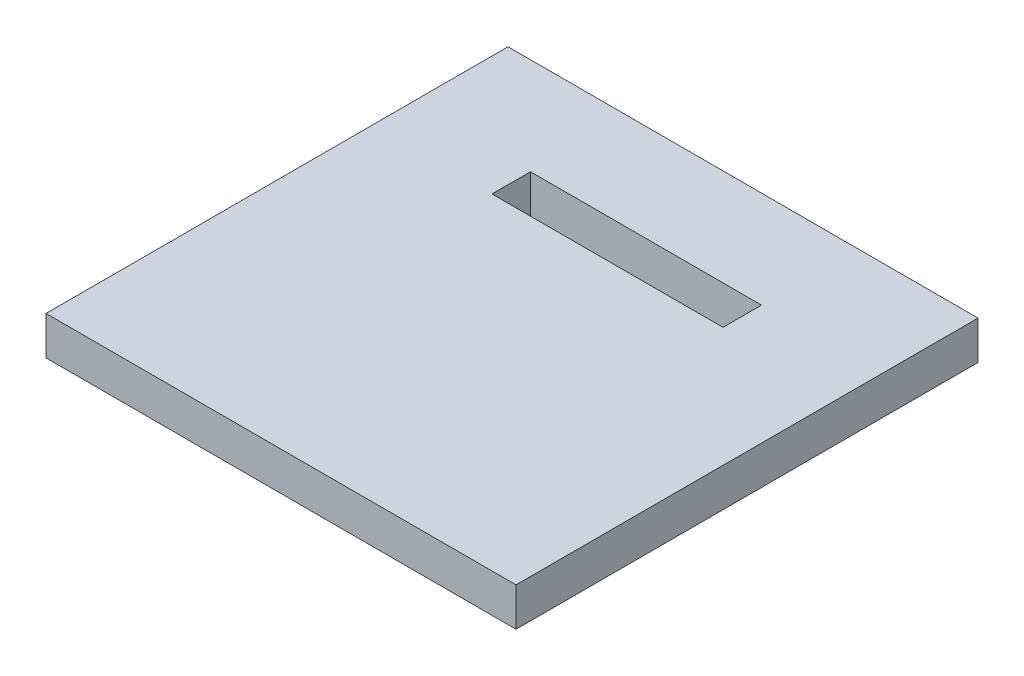
SolidWorks part; units mm, degrees
ref_plane "Front Plane" through (0, 0, 0) normal (0, 0, 1) x (1, 0, 0)
ref_plane "Top Plane" through (0, 0, 0) normal (0, 1, 0) x (1, 0, 0)
ref_plane "Right Plane" through (0, 0, 0) normal (1, 0, 0) x (0, 0, -1)
sketch "Sketch1" plane through (0, 0, 0) normal (0, 1, 0) x (1, 0, 0)
  line L0 (19.3802, 30.099) -> (19.3802, 38.1) construction
  line L1 (0, 0) -> (38.7604, 0)
  line L2 (0, 0) -> (0, 38.1)
  line L3 (0, 38.1) -> (38.7604, 38.1)
  line L4 (38.7604, 0) -> (38.7604, 38.1)
  line L5 (9.8552, 30.099) -> (28.9052, 30.099)
  line L6 (9.8552, 30.099) -> (9.8552, 26.924)
  line L7 (9.8552, 26.924) -> (28.9052, 26.924)
  line L8 (28.9052, 30.099) -> (28.9052, 26.924)
  dimension "D1" = 38.1
  dimension "D2" = 38.7604
  dimension "D3" = 26.924
  dimension "D4" = 19.05
  dimension "D5" = 3.175
extrude "Boss-Extrude1" add sketch "Sketch1" along normal blind 3.175
